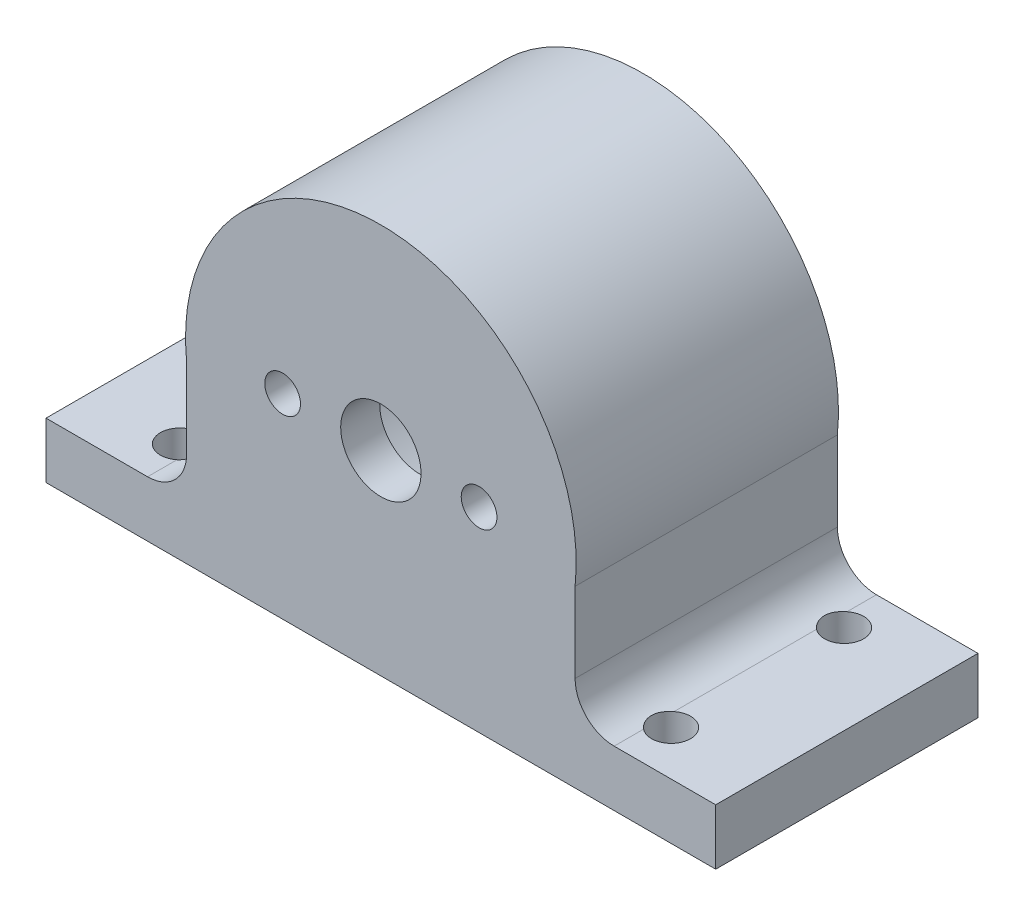
SolidWorks part; units mm, degrees
ref_plane "Płaszczyzna przednia" through (0, 0, 0) normal (0, 0, 1) x (1, 0, 0)
ref_plane "Płaszczyzna górna" through (0, 0, 0) normal (0, 1, 0) x (1, 0, 0)
ref_plane "Płaszczyzna prawa" through (0, 0, 0) normal (1, 0, 0) x (0, 0, -1)
sketch "Szkic1" plane through (0, 0, 0) normal (0, 0, 1) x (1, 0, 0)
  circle A0 centre (0, 0) radius 12.6
  circle A1 centre (0, 0) radius 17.5
  dimension "D1" = 25.2
  dimension "D2" = 35
extrude "Dodanie-wyciągnięcie1" add sketch "Szkic1" along normal blind 20
sketch "Szkic2" plane through (0, 0, 20) normal (0, 0, 1) x (1, 0, 0)
  circle A0 centre (0, 0) radius 17.5 construction
  circle A1 centre (0, 0) radius 17.5
  point P4 (0, 0)
extrude "Dodanie-wyciągnięcie2" add sketch "Szkic2" along normal blind 3.5
sketch "Szkic3" plane through (0, 0, 23.5) normal (0, 0, 1) x (1, 0, 0)
  line L0 (-30, -17.5) -> (30, -17.5)
  line L1 (30, -17.5) -> (30, -12.5)
  line L2 (30, -12.5) -> (20.902, -12.5)
  line L3 (17.402, -9) -> (17.402, -1.8493)
  line L4 (0, 17.9958) -> (0, 17.5) construction
  line L5 (-17.402, -9) -> (-17.402, -1.8493)
  line L6 (-30, -12.5) -> (-20.902, -12.5)
  line L7 (-30, -17.5) -> (-30, -12.5)
  line L8 (0, -17.5) -> (0, -20.0884) construction
  circle A0 centre (0, 0) radius 17.5 construction
  arc A1 (-17.402, -1.8493) -> (17.402, -1.8493) centre (0, 0) ccw
  arc A2 (20.902, -12.5) -> (17.402, -9) centre (20.902, -9) cw
  arc A3 (-20.902, -12.5) -> (-17.402, -9) centre (-20.902, -9) ccw
  point P20 (0, -17.5)
  circle M7 centre (0, 0) radius 17.5
  dimension "D3" = 3.5
  dimension "D1" = 30
  dimension "D2" = 5
extrude "Dodanie-wyciągnięcie3" add sketch "Szkic3" against normal up to surface (23.5 mm away) contours A3 L6 L7 L0 L5 M7 | L2 A2 L3 L0 L1 M7 up to face at (17.5, 0, 0)
sketch "Szkic4" plane through (0, 0, 20) normal (0, 0, -1) x (-1, 0, 0)
  line L0 (0, 20.8819) -> (0, -23.2842) construction
  line L1 (-23.2534, 0) -> (31.8156, 0) construction
  circle A0 centre (0, 0) radius 3.6
  circle A1 centre (-8.8, 0) radius 1.6
  circle A2 centre (0, 0) radius 12.6 construction
  circle A3 centre (0, 0) radius 12.6 construction
  circle A4 centre (8.8, 0) radius 1.6
  point P8 (-12.6, 0)
  dimension "D1" = 7.2
  dimension "D2" = 3.2
  dimension "D3" = 3.8
extrude "Wytnij-wyciągnięcie1" cut sketch "Szkic4" against normal through all
sketch "Szkic5" plane through (0, -17.5, 0) normal (0, -1, 0) x (1, 0, 0)
  line L0 (30, 0) -> (-30, 0) construction
  line L1 (0, -3.5772) -> (0, 33.4435) construction
  line L2 (-32.2468, 11.75) -> (39.1458, 11.75) construction
  line L3 (-30, 0) -> (-30, 23.5) construction
  circle A0 centre (-22, 4) radius 1.75
  circle A1 centre (22, 4) radius 1.75
  circle A2 centre (22, 19.5) radius 1.75
  circle A3 centre (-22, 19.5) radius 1.75
  point P15 (-21.8983, -11.8269)
  point P19 (-30, 11.75)
  dimension "3,5" = 3.5
  dimension "D2" = 4
  dimension "D3" = 22
extrude "Wytnij-wyciągnięcie2" cut sketch "Szkic5" against normal through all
sketch "Szkic6" plane through (0, 0, 23.5) normal (0, 0, 1) x (1, 0, 0)
  line L0 (0, 19.0955) -> (0, -22.7914) construction
